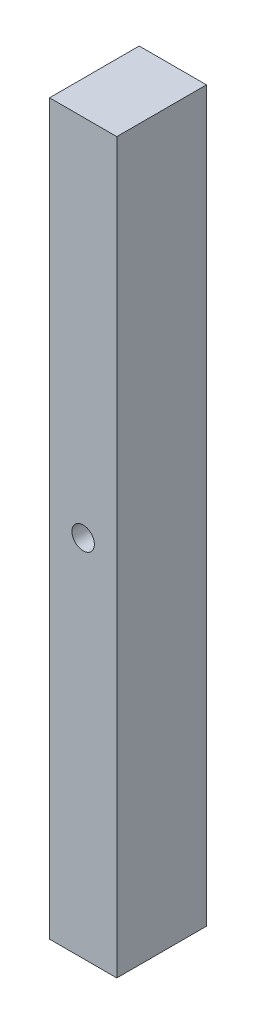
SolidWorks part; units mm, degrees
ref_plane "Front Plane" through (0, 0, 0) normal (0, 0, 1) x (1, 0, 0)
ref_plane "Top Plane" through (0, 0, 0) normal (0, 1, 0) x (1, 0, 0)
ref_plane "Right Plane" through (0, 0, 0) normal (1, 0, 0) x (0, 0, -1)
sketch "Sketch1" plane through (0, 0, 0) normal (0, 0, 1) x (1, 0, 0)
  line L1 (4.3112, -11.9388) -> (-1.6888, -11.9388)
  line L2 (4.3112, -11.9388) -> (4.3112, 53.0612)
  line L3 (4.3112, 53.0612) -> (-1.6888, 53.0612)
  line L4 (-1.6888, -11.9388) -> (-1.6888, 53.0612)
  circle A0 centre (1.3112, 20.5612) radius 1
  dimension "D3" = 2
  dimension "D1" = 6
  dimension "D2" = 65
  dimension "D4" = 3
  dimension "D5" = 3
  dimension "D6" = 32.5
  dimension "D7" = 32.5
extrude "Boss-Extrude1" add sketch "Sketch1" along normal blind 8
